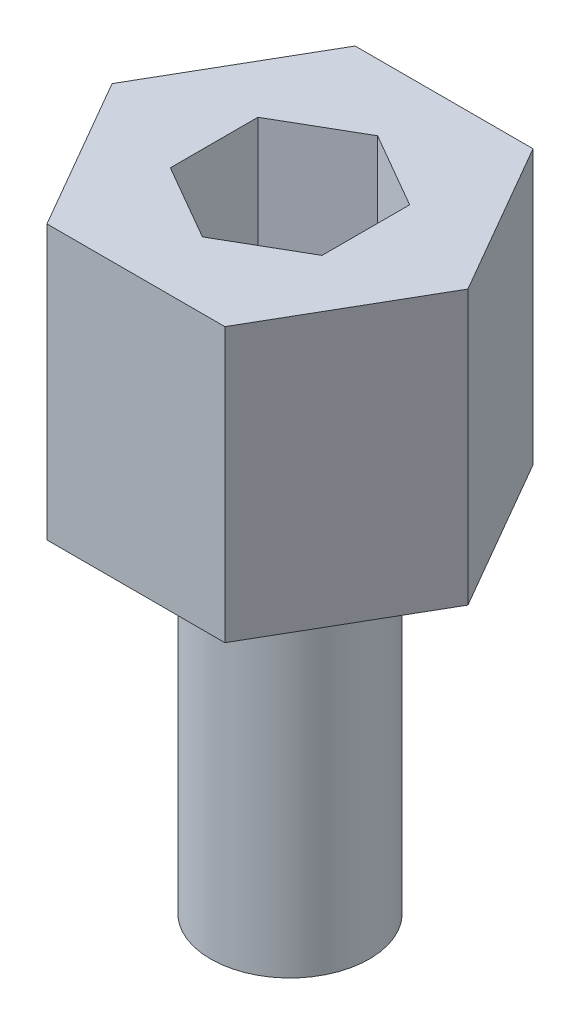
SolidWorks part; units mm, degrees
ref_plane "Front Plane" through (0, 0, 0) normal (0, 0, 1) x (1, 0, 0)
ref_plane "Top Plane" through (0, 0, 0) normal (0, 1, 0) x (1, 0, 0)
ref_plane "Right Plane" through (0, 0, 0) normal (1, 0, 0) x (0, 0, -1)
sketch "Sketch1" plane through (0, 0, 0) normal (0, 1, 0) x (1, 0, 0)
  circle A0 centre (0, 0) radius 2.9
  dimension "D1" = 5.8
extrude "Boss-Extrude1" add sketch "Sketch1" along normal blind 13
sketch "Sketch2" plane through (0, 13, 0) normal (0, 1, 0) x (1, 0, 0)
  line L1 (6.5, 0) -> (3.25, 5.6292)
  line L2 (3.25, 5.6292) -> (-3.25, 5.6292)
  line L3 (-3.25, 5.6292) -> (-6.5, 0)
  line L4 (-6.5, 0) -> (-3.25, -5.6292)
  line L5 (-3.25, -5.6292) -> (3.25, -5.6292)
  line L6 (3.25, -5.6292) -> (6.5, 0)
  circle A0 centre (0, 0) radius 5.6292 construction
  dimension "D1" = 6.5
extrude "Boss-Extrude2" add sketch "Sketch2" along normal blind 10
sketch "Sketch3" plane through (0, 0, 0) normal (0, -1, 0) x (1, 0, 0)
  circle A0 centre (0, 0) radius 1.6
extrude "Cut-Extrude1" cut sketch "Sketch3" against normal blind 25
sketch "Sketch4" plane through (0, 23, 0) normal (0, 1, 0) x (1, 0, 0)
  line L1 (0, 3.2) -> (-2.7713, 1.6)
  line L2 (-2.7713, 1.6) -> (-2.7713, -1.6)
  line L3 (-2.7713, -1.6) -> (0, -3.2)
  line L4 (0, -3.2) -> (2.7713, -1.6)
  line L5 (2.7713, -1.6) -> (2.7713, 1.6)
  line L6 (2.7713, 1.6) -> (0, 3.2)
  circle A0 centre (0, 0) radius 2.7713 construction
  dimension "D1" = 3.2
extrude "Cut-Extrude2" cut sketch "Sketch4" against normal blind 7
